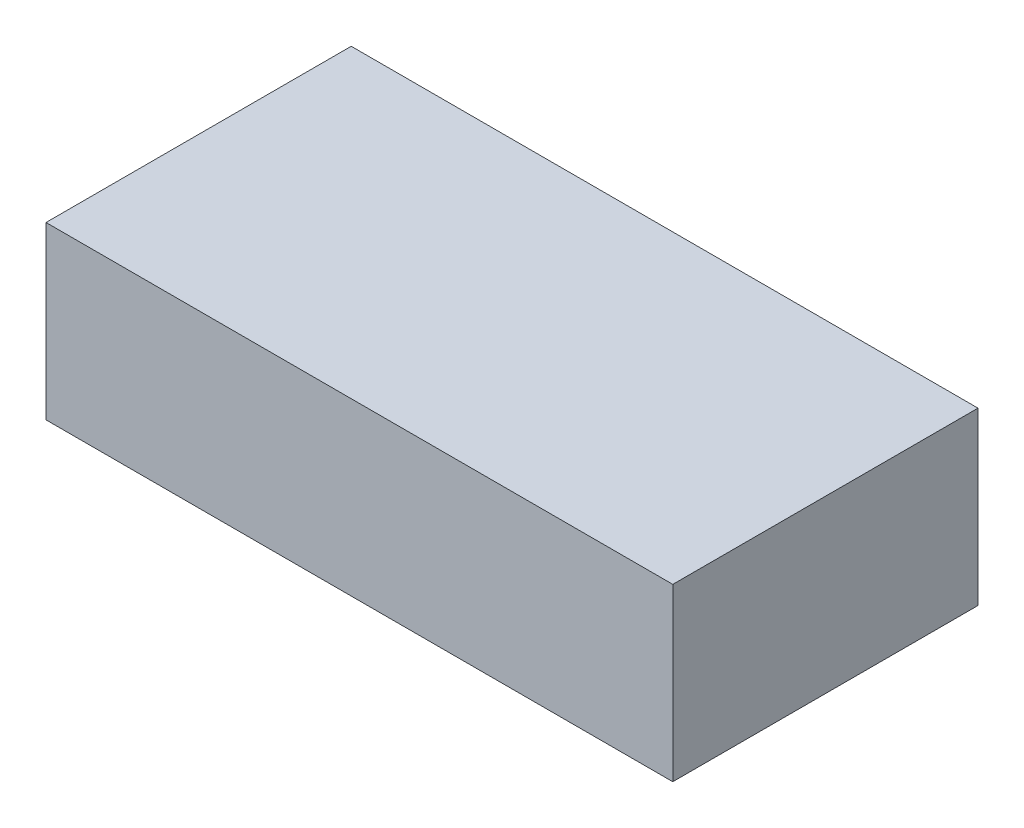
SolidWorks part; units mm, degrees
ref_plane "Front Plane" through (0, 0, 0) normal (0, 0, 1) x (1, 0, 0)
ref_plane "Top Plane" through (0, 0, 0) normal (0, 1, 0) x (1, 0, 0)
ref_plane "Right Plane" through (0, 0, 0) normal (1, 0, 0) x (0, 0, -1)
sketch "Sketch1" plane through (0, 0, 0) normal (0, 0, 1) x (1, 0, 0)
  line L1 (0, 0) -> (33, 0)
  line L2 (0, 0) -> (0, 9)
  line L3 (0, 9) -> (33, 9)
  line L4 (33, 0) -> (33, 9)
  dimension "D1" = 9
  dimension "D2" = 33
extrude "Boss-Extrude1" add sketch "Sketch1" along normal blind 32.1391
sketch "Sketch2" plane through (0, 9, 0) normal (0, 1, 0) x (1, 0, 0)
  line L0 (0, 0) -> (33, -32.1391) construction
  line L1 (33, -32.1391) -> (0, -32.1391) construction
  line L2 (0, -32.1391) -> (33, 0) construction
  line L3 (0, -16.0695) -> (33, -16.0695)
  line L4 (0, -32.1391) -> (0, 0) construction
  line L5 (33, -32.1391) -> (33, 0) construction
  line L6 (33, -16.0695) -> (33, -32.1391)
  line L7 (33, -32.1391) -> (0, -32.1391)
  line L8 (0, -32.1391) -> (0, -16.0695)
extrude "Cut-Extrude1" cut sketch "Sketch2" against normal through all
